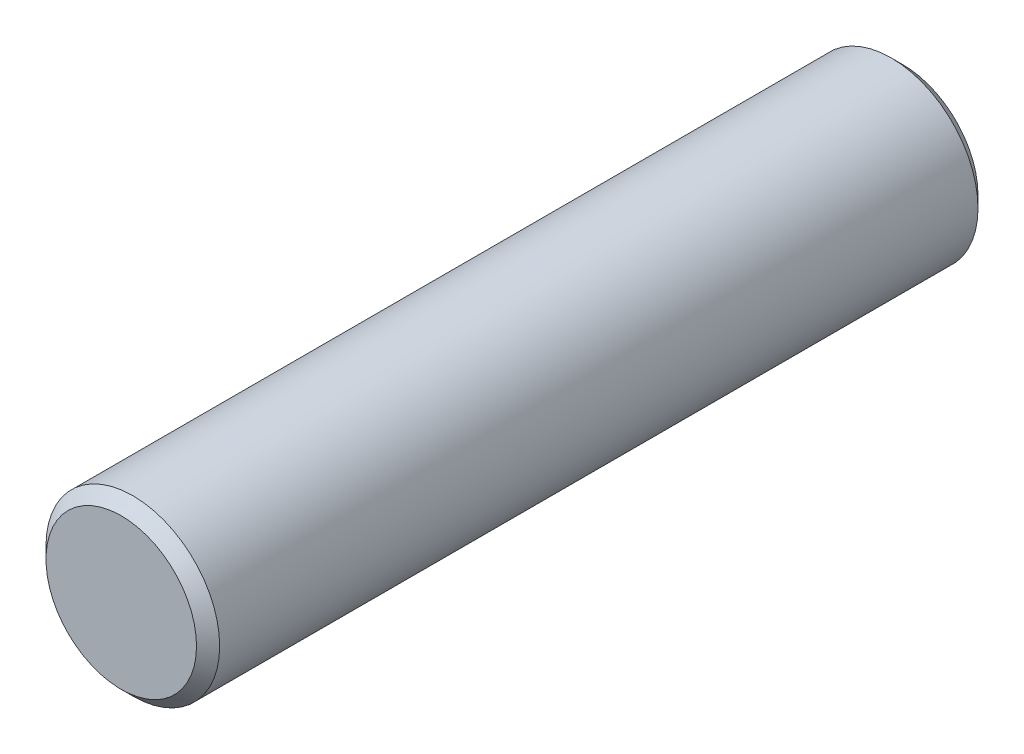
SolidWorks part; units mm, degrees
ref_plane "Front Plane" through (0, 0, 0) normal (0, 0, 1) x (1, 0, 0)
ref_plane "Top Plane" through (0, 0, 0) normal (0, 1, 0) x (1, 0, 0)
ref_plane "Right Plane" through (0, 0, 0) normal (1, 0, 0) x (0, 0, -1)
sketch "Sketch2" plane through (0, 0, 0) normal (0, 0, 1) x (1, 0, 0)
  circle A0 centre (0, 0) radius 1.5
  dimension "D1" = 3
extrude "Boss-Extrude1" add sketch "Sketch2" along normal blind 13.5
chamfer "Chamfer1" distance 0.2 angle 45 2 edges at (1.5, 0, 0) (1.5, 0, 13.5)
